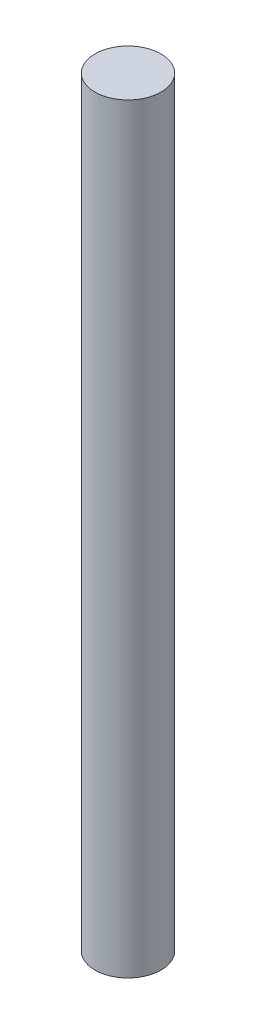
SolidWorks part; units mm, degrees
ref_plane "Front Plane" through (0, 0, 0) normal (0, 0, 1) x (1, 0, 0)
ref_plane "Top Plane" through (0, 0, 0) normal (0, 1, 0) x (1, 0, 0)
ref_plane "Right Plane" through (0, 0, 0) normal (1, 0, 0) x (0, 0, -1)
sketch "Sketch1" plane through (0, 0, 0) normal (0, 1, 0) x (1, 0, 0)
  circle A0 centre (0, 0) radius 5
extrude "Boss-Extrude1" add sketch "Sketch1" along normal blind 115
